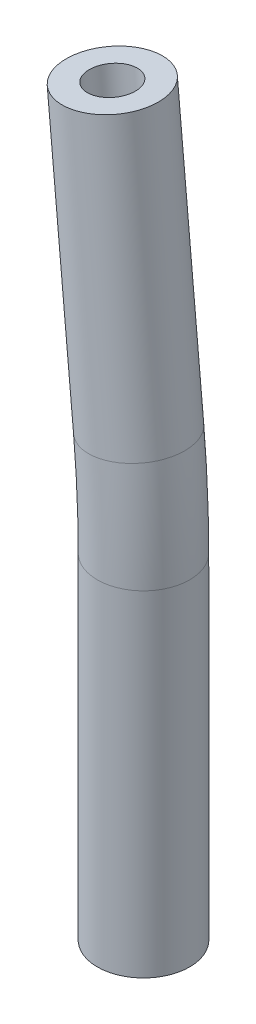
SolidWorks part; units mm, degrees
material "PTFE (general)"
ref_plane "Front Plane" through (0, 0, 0) normal (0, 0, 1) x (1, 0, 0)
ref_plane "Top Plane" through (0, 0, 0) normal (0, 1, 0) x (1, 0, 0)
ref_plane "Right Plane" through (0, 0, 0) normal (1, 0, 0) x (0, 0, -1)
sketch "Sketch1" plane through (0, 0, 0) normal (0, 0, 1) x (1, 0, 0)
  line L0 (0.0519, -2.2769) -> (0.0519, -16.7969)
  line L1 (-0.1555, 2.2721) -> (-1.2982, 14.7801)
  arc A0 (-0.1555, 2.2721) -> (0.0519, -2.2769) centre (-49.9481, -2.2769) cw
  point P4 (0, 0)
  point P5 (0.0519, -19.9712)
  dimension "D2" = 185.22
  dimension "D3" = 12.56
  dimension "D1" = 50
  dimension "D4" = 14.52
ref_plane "Plane1" through (0, -16.7969, 0) normal (0, 1, 0) x (1, 0, 0)
sketch "Sketch2" plane through (0, -16.7969, 0) normal (0, 1, 0) x (1, 0, 0)
  circle A0 centre (0.0519, 0) radius 1
  circle A1 centre (0.0519, 0) radius 2
  dimension "D1" = 2
  dimension "D2" = 4
sweep "Sweep1" add profiles "Sketch2" path "Sketch1"
